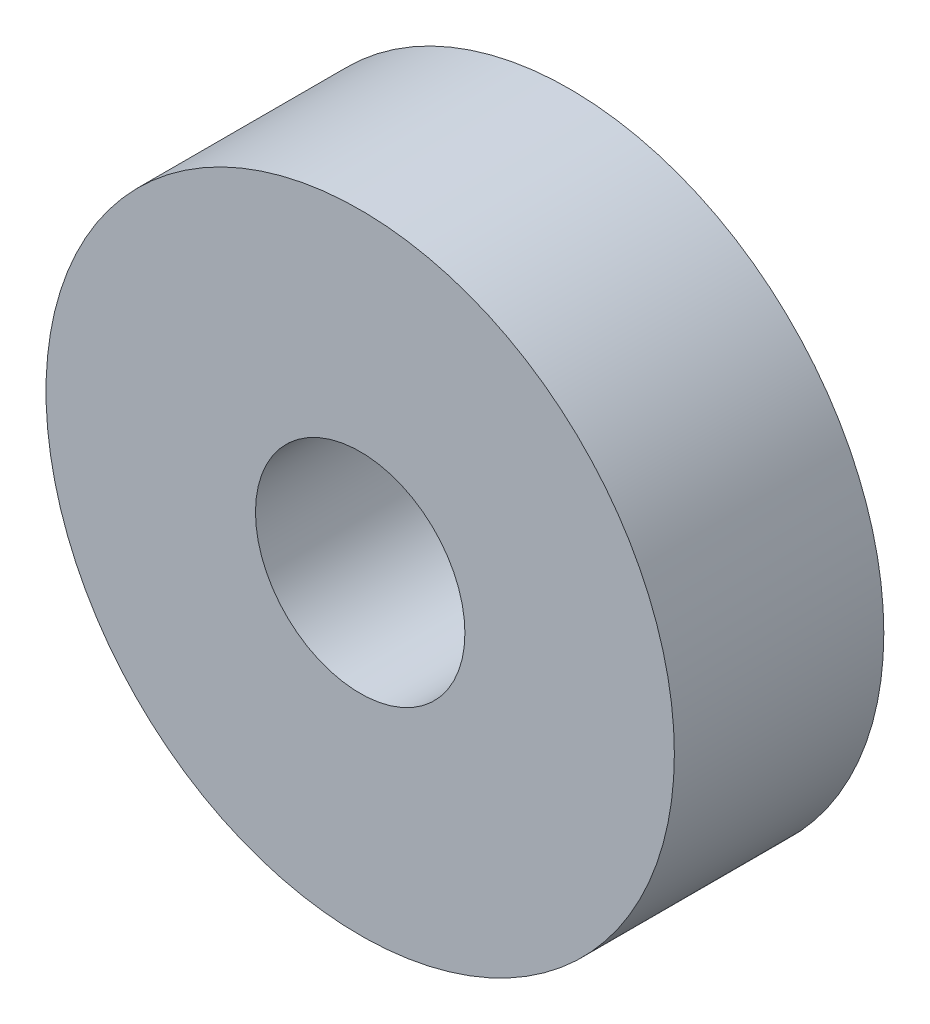
SolidWorks part; units mm, degrees
ref_plane "Front Plane" through (0, 0, 0) normal (0, 0, 1) x (1, 0, 0)
ref_plane "Top Plane" through (0, 0, 0) normal (0, 1, 0) x (1, 0, 0)
ref_plane "Right Plane" through (0, 0, 0) normal (1, 0, 0) x (0, 0, -1)
sketch "Sketch2" plane through (0, 0, 0) normal (0, 0, 1) x (1, 0, 0)
  circle A0 centre (0, 0) radius 6
  circle A1 centre (0, 0) radius 2
  dimension "D1" = 12
  dimension "D2" = 4
extrude "Boss-Extrude1" add sketch "Sketch2" along normal mid plane 4
